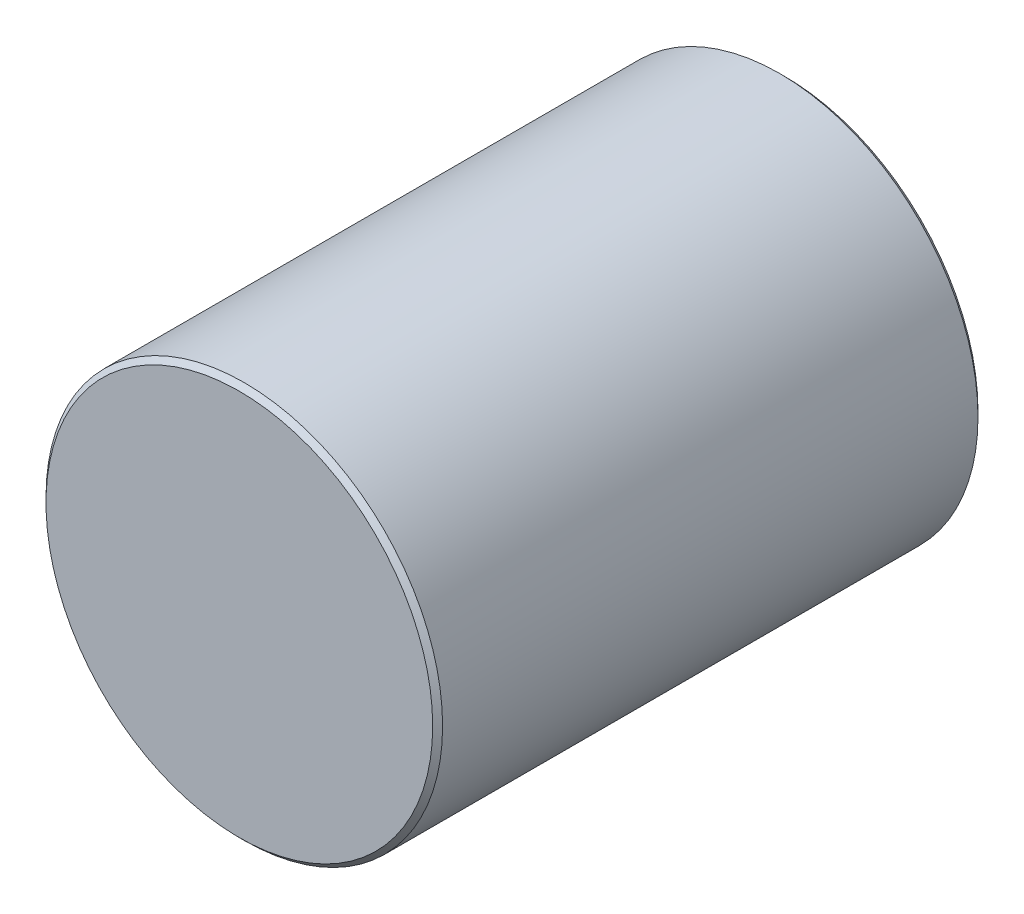
SolidWorks part; units mm, degrees
ref_plane "Ön Düzlem" through (0, 0, 0) normal (0, 0, 1) x (1, 0, 0)
ref_plane "Üst Düzlem" through (0, 0, 0) normal (0, 1, 0) x (1, 0, 0)
ref_plane "Sağ Düzlem" through (0, 0, 0) normal (1, 0, 0) x (0, 0, -1)
sketch "Çizim1" plane through (0, 0, 0) normal (0, 0, 1) x (1, 0, 0)
  circle A0 centre (0, 0) radius 4
  dimension "D1" = 8
extrude "Yükseklik-Ekstrüzyon1" add sketch "Çizim1" along normal blind 11
chamfer "Pah1" distance 0.1 angle 45 2 edges at (4, 0, 0) (4, 0, 11)
